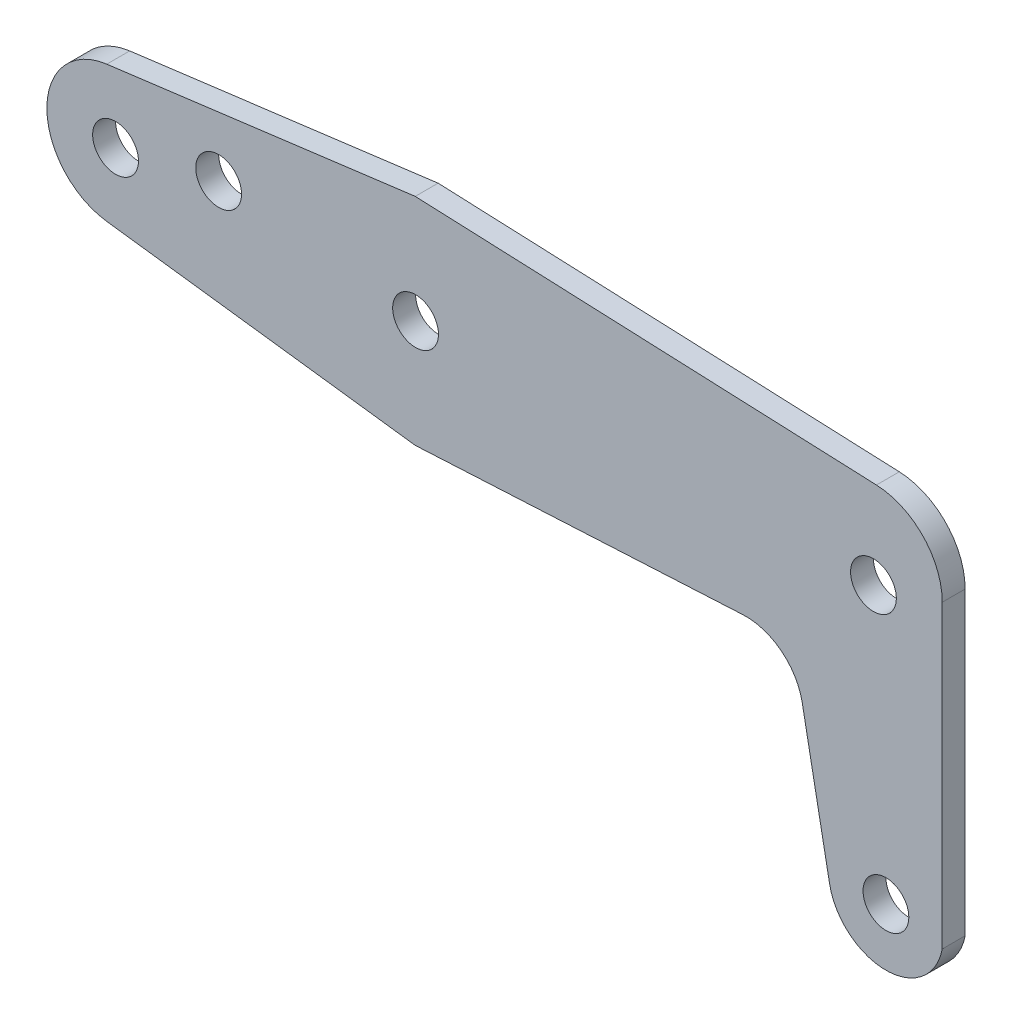
SolidWorks part; units mm, degrees
ref_plane "Front Plane" through (0, 0, 0) normal (0, 0, 1) x (1, 0, 0)
ref_plane "Top Plane" through (0, 0, 0) normal (0, 1, 0) x (1, 0, 0)
ref_plane "Right Plane" through (0, 0, 0) normal (1, 0, 0) x (0, 0, -1)
sketch "Sketch1" plane through (0, 0, 0) normal (0, 0, 1) x (1, 0, 0)
  line L0 (-42.8232, 9.447) -> (-0.0462, 14.9548)
  line L9 (0, 0) -> (-49.0191, 0) construction
  line L10 (-42.8232, -9.447) -> (-0.0462, -14.9548)
  line L11 (-0.0462, 14.9548) -> (63.9147, 12.2692)
  line L12 (-0.0462, -14.9548) -> (45.3983, -12.5651)
  line L13 (53.6248, -19.0128) -> (57.4221, -38.8939)
  line L15 (73.0402, -38.8939) -> (73.0402, 2.7526)
  arc A1 (-42.8232, 9.447) -> (-42.8232, -9.447) centre (-41.6069, 0) ccw
  arc A2 (45.3983, -12.5651) -> (53.6248, -19.0128) centre (45.8158, -20.5043) cw
  arc A3 (63.9147, 12.2692) -> (73.0402, 2.7526) centre (63.5152, 2.7526) cw
  arc A4 (57.4221, -38.8939) -> (73.0402, -38.8939) centre (65.2311, -37.4024) ccw
  dimension "D1" = 9.525
  dimension "D2" = 7.9502
  dimension "D3" = 9.525
  dimension "D4" = 7.9502
extrude "Boss-Extrude1" add sketch "Sketch1" along normal blind 3.175
sketch "Sketch2" plane through (0, 0, 3.175) normal (0, 0, 1) x (1, 0, 0)
  circle A0 centre (-41.6069, 0) radius 3.175
  circle A1 centre (-27.3067, 3.175) radius 3.175
  circle A2 centre (0, 0) radius 3.175
  circle A4 centre (63.5, 0.0372) radius 3.175
  circle A5 centre (65.2311, -37.4024) radius 3.175
  dimension "D1" = 6.35
  dimension "D2" = 14.3002
  dimension "D3" = 3.175
  dimension "D4" = 63.5
  dimension "D5" = 19.05
extrude "Cut-Extrude1" cut sketch "Sketch2" against normal through all
